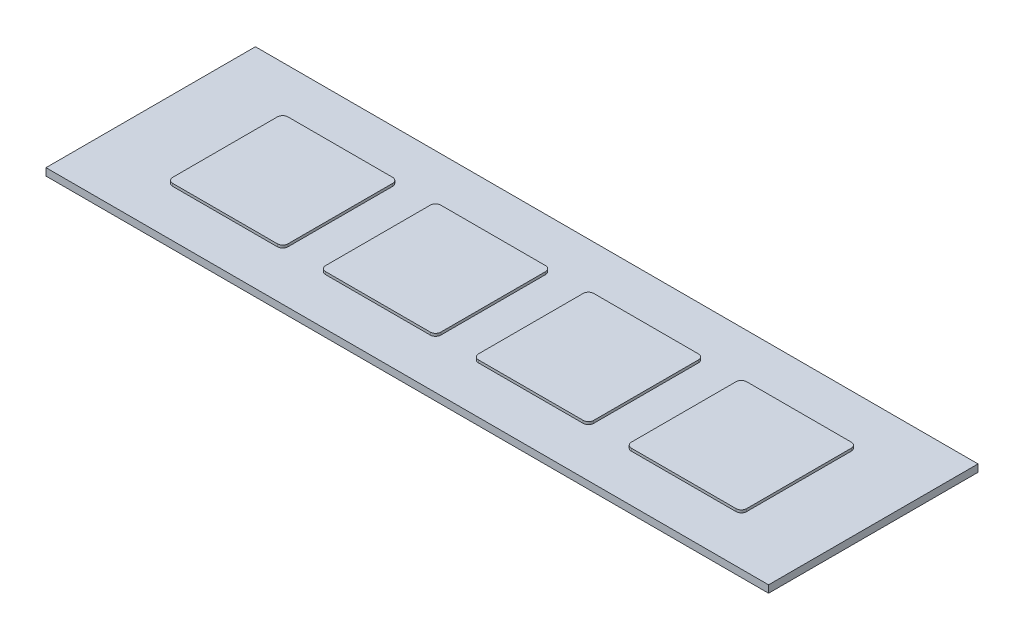
SolidWorks part; units mm, degrees
ref_plane "Front Plane" through (0, 0, 0) normal (0, 0, 1) x (1, 0, 0)
ref_plane "Top Plane" through (0, 0, 0) normal (0, 1, 0) x (1, 0, 0)
ref_plane "Right Plane" through (0, 0, 0) normal (1, 0, 0) x (0, 0, -1)
sketch "Sketch1" plane through (0, 0, 0) normal (0, 1, 0) x (1, 0, 0)
  line L1 (-34.5, -10) -> (34.5, -10)
  line L2 (-34.5, -10) -> (-34.5, 10)
  line L3 (-34.5, 10) -> (34.5, 10)
  line L4 (34.5, -10) -> (34.5, 10)
  line L5 (-34.5, -10) -> (34.5, 10) construction
  line L6 (-34.5, 10) -> (34.5, -10) construction
  point P0 (0, 0)
  dimension "D1" = 20
  dimension "D2" = 69
extrude "Boss-Extrude1" add sketch "Sketch1" along normal blind 0.7
sketch "Sketch2" plane through (0, 0.7, 0) normal (0, 1, 0) x (1, 0, 0)
  line L1 (-26.9, -5.5) -> (-16.9, -5.5)
  line L2 (-27.4, -5) -> (-27.4, 5)
  line L3 (-26.9, 5.5) -> (-16.9, 5.5)
  line L4 (-16.4, -5) -> (-16.4, 5)
  line L5 (-27.4, -5.5) -> (-16.4, 5.5) construction
  line L6 (-27.4, 5.5) -> (-16.4, -5.5) construction
  line L7 (-12.3, -5.5) -> (-2.3, -5.5)
  line L8 (-12.8, -5) -> (-12.8, 5)
  line L9 (-12.3, 5.5) -> (-2.3, 5.5)
  line L10 (-1.8, -5) -> (-1.8, 5)
  line L11 (-12.8, -5.5) -> (-1.8, 5.5) construction
  line L12 (-12.8, 5.5) -> (-1.8, -5.5) construction
  line L13 (2.3, -5.5) -> (12.3, -5.5)
  line L14 (1.8, -5) -> (1.8, 5)
  line L15 (2.3, 5.5) -> (12.3, 5.5)
  line L16 (12.8, -5) -> (12.8, 5)
  line L17 (1.8, -5.5) -> (12.8, 5.5) construction
  line L18 (1.8, 5.5) -> (12.8, -5.5) construction
  line L19 (16.9, -5.5) -> (26.9, -5.5)
  line L20 (16.4, -5) -> (16.4, 5)
  line L21 (16.9, 5.5) -> (26.9, 5.5)
  line L22 (27.4, -5) -> (27.4, 5)
  line L23 (16.4, -5.5) -> (27.4, 5.5) construction
  line L24 (16.4, 5.5) -> (27.4, -5.5) construction
  arc A0 (26.9, -5.5) -> (27.4, -5) centre (26.9, -5) ccw
  arc A1 (26.9, 5.5) -> (27.4, 5) centre (26.9, 5) cw
  arc A2 (16.4, 5) -> (16.9, 5.5) centre (16.9, 5) cw
  arc A3 (16.9, -5.5) -> (16.4, -5) centre (16.9, -5) cw
  arc A4 (12.3, -5.5) -> (12.8, -5) centre (12.3, -5) ccw
  arc A5 (12.3, 5.5) -> (12.8, 5) centre (12.3, 5) cw
  arc A6 (1.8, 5) -> (2.3, 5.5) centre (2.3, 5) cw
  arc A7 (2.3, -5.5) -> (1.8, -5) centre (2.3, -5) cw
  arc A8 (-12.3, -5.5) -> (-12.8, -5) centre (-12.3, -5) cw
  arc A9 (-2.3, -5.5) -> (-1.8, -5) centre (-2.3, -5) ccw
  arc A10 (-2.3, 5.5) -> (-1.8, 5) centre (-2.3, 5) cw
  arc A11 (-12.8, 5) -> (-12.3, 5.5) centre (-12.3, 5) cw
  arc A12 (-26.9, -5.5) -> (-27.4, -5) centre (-26.9, -5) cw
  arc A13 (-16.9, -5.5) -> (-16.4, -5) centre (-16.9, -5) ccw
  arc A14 (-16.9, 5.5) -> (-16.4, 5) centre (-16.9, 5) cw
  arc A15 (-27.4, 5) -> (-26.9, 5.5) centre (-26.9, 5) cw
  point P0 (-21.9, 0)
  point P5 (-7.3, 0)
  point P10 (7.3, 0)
  point P15 (21.9, 0)
  point P20 (0, 0)
  point P22 (0, 0)
  dimension "D7" = 0.5
  dimension "D1" = 1.8
  dimension "D2" = 1.8
  dimension "D3" = 3.6
  dimension "D4" = 3.6
  dimension "D5" = 11
  dimension "D6" = 11
extrude "Boss-Extrude2" add sketch "Sketch2" along normal blind 0.25
